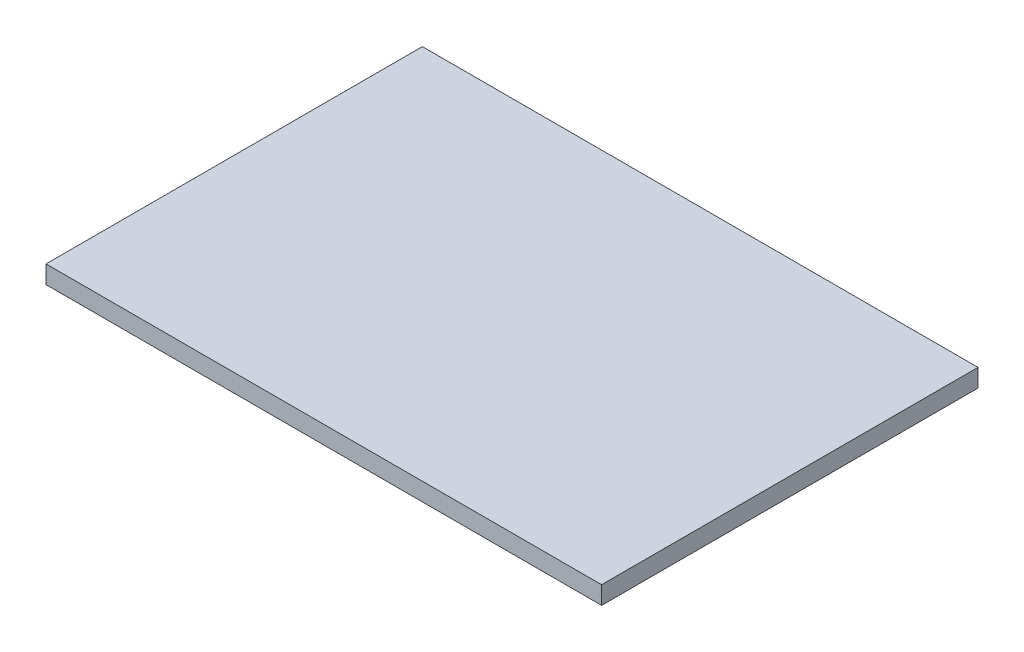
SolidWorks part; units mm, degrees
ref_plane "Front Plane" through (0, 0, 0) normal (0, 0, 1) x (1, 0, 0)
ref_plane "Top Plane" through (0, 0, 0) normal (0, 1, 0) x (1, 0, 0)
ref_plane "Right Plane" through (0, 0, 0) normal (1, 0, 0) x (0, 0, -1)
sketch "Sketch1" plane through (0, 0, 0) normal (0, 1, 0) x (1, 0, 0)
  line L1 (0, 0) -> (155, 0)
  line L2 (0, 0) -> (0, 105)
  line L3 (0, 105) -> (155, 105)
  line L4 (155, 0) -> (155, 105)
  dimension "D1" = 155
  dimension "D2" = 105
extrude "Boss-Extrude1" add sketch "Sketch1" along normal blind 5
